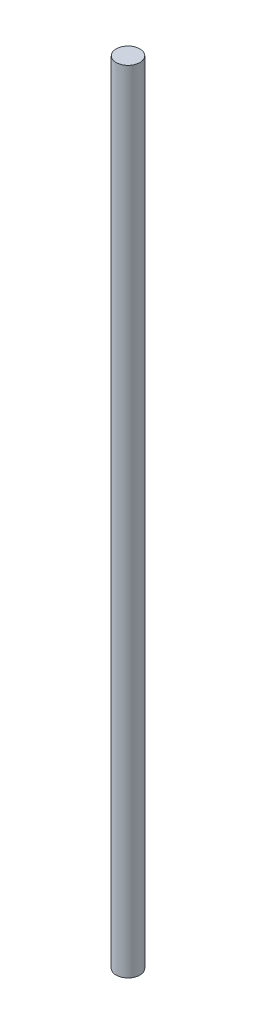
SolidWorks part; units mm, degrees
ref_plane "Спереди" through (0, 0, 0) normal (0, 0, 1) x (1, 0, 0)
ref_plane "Сверху" through (0, 0, 0) normal (0, 1, 0) x (1, 0, 0)
ref_plane "Справа" through (0, 0, 0) normal (1, 0, 0) x (0, 0, -1)
sketch "Sketch1" plane through (0, 0, 0) normal (0, 1, 0) x (1, 0, 0)
  circle A0 centre (0, -1.6046) radius 3
  dimension "D1" = 6
extrude "Boss-Extrude1" add sketch "Sketch1" along normal blind 200
